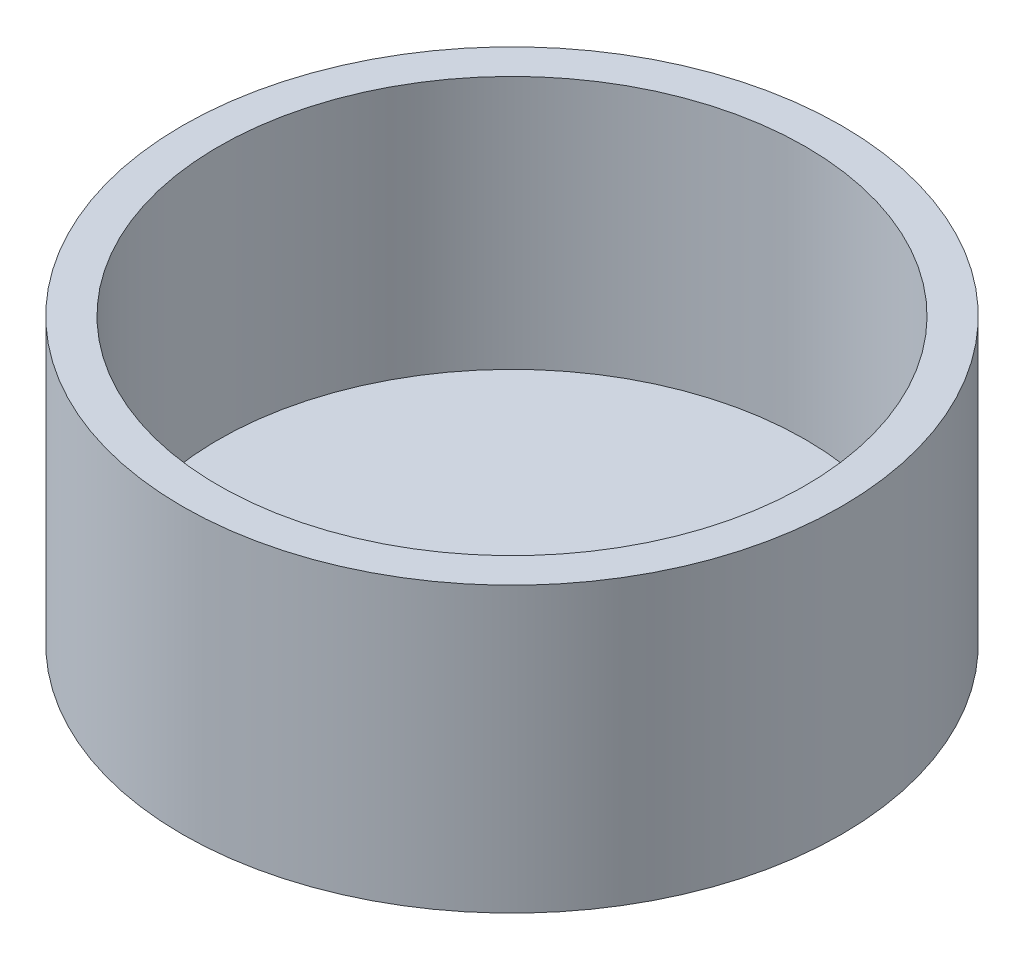
SolidWorks part; units mm, degrees
ref_plane "Front Plane" through (0, 0, 0) normal (0, 0, 1) x (1, 0, 0)
ref_plane "Top Plane" through (0, 0, 0) normal (0, 1, 0) x (1, 0, 0)
ref_plane "Right Plane" through (0, 0, 0) normal (1, 0, 0) x (0, 0, -1)
sketch "Sketch1" plane through (0, 0, 0) normal (0, 0, 1) x (1, 0, 0)
  line L0 (0, 0) -> (0, 5.9)
  line L1 (0, 5.9) -> (57.15, 5.9)
  line L2 (57.15, 5.9) -> (57.15, 55.3)
  line L3 (57.15, 55.3) -> (64.2, 55.3)
  line L4 (64.2, 55.3) -> (64.2, 0)
  line L5 (64.2, 0) -> (0, 0)
  line L6 (0, 0) -> (0, 59.071) construction
  dimension "D1" = 114.3
  dimension "D2" = 128.4
  dimension "D3" = 55.3
  dimension "D4" = 5.9
revolve "Revolve1" add sketch "Sketch1" angle 360 about L6
